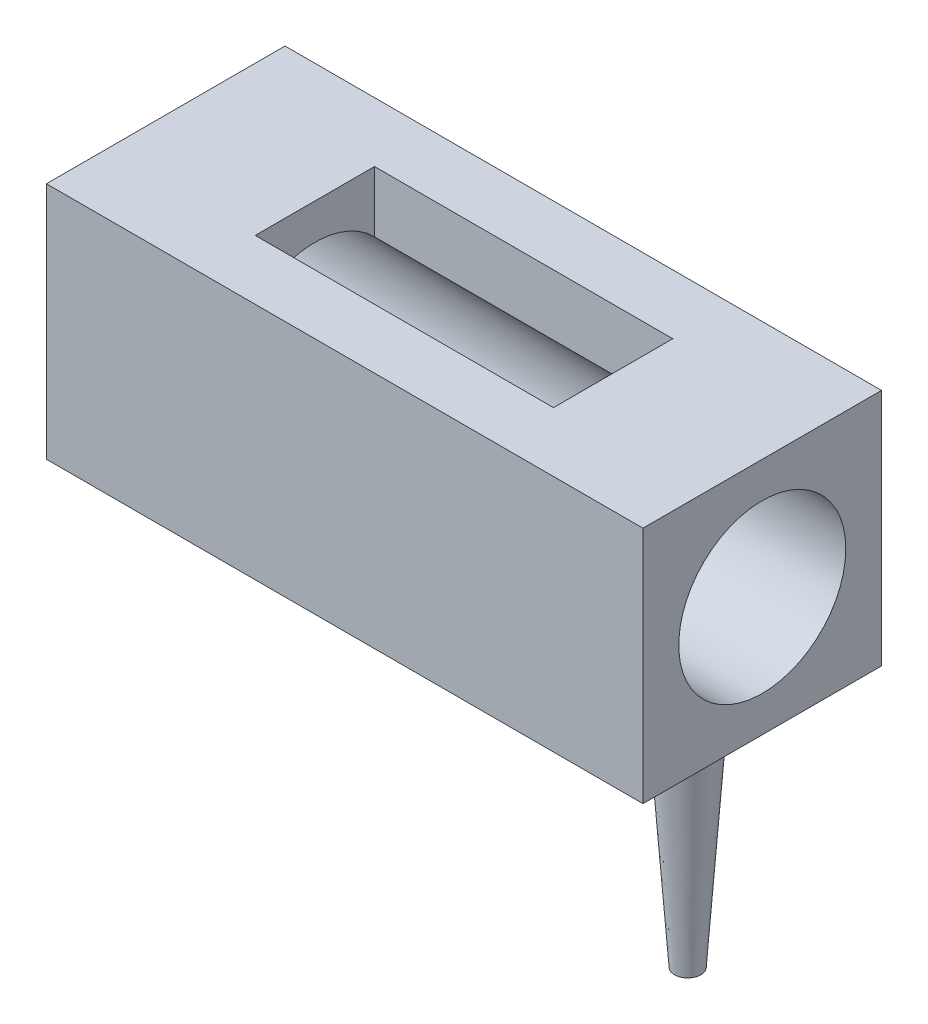
SolidWorks part; units mm, degrees
ref_plane "Alzado" through (0, 0, 0) normal (0, 0, 1) x (1, 0, 0)
ref_plane "Planta" through (0, 0, 0) normal (0, 1, 0) x (1, 0, 0)
ref_plane "Vista lateral" through (0, 0, 0) normal (1, 0, 0) x (0, 0, -1)
sketch "Croquis1" plane through (0, 0, 0) normal (0, 0, 1) x (1, 0, 0)
  line L1 (0, 0) -> (1000, 0)
  line L2 (0, 0) -> (0, 400)
  line L3 (0, 400) -> (1000, 400)
  line L4 (1000, 0) -> (1000, 400)
  dimension "D1" = 400
  dimension "D2" = 1000
extrude "Saliente-Extruir1" add sketch "Croquis1" along normal blind 400
sketch "Croquis2" plane through (1000, 0, 0) normal (1, 0, 0) x (0, 0, -1)
  line L0 (-400, 0) -> (-400, 400) construction
  line L1 (-400, 400) -> (0, 400) construction
  circle A0 centre (-200, 200) radius 140
  point P4 (0, 0)
  point P5 (0, 0)
  point P6 (0, 0)
  dimension "D1" = 200
  dimension "D2" = 200
extrude "Cortar-Extruir1" cut sketch "Croquis2" against normal blind 1000 contours A0
sketch "Croquis3" plane through (0, 0, 0) normal (0, -1, 0) x (1, 0, 0)
  line L0 (0, 400) -> (0, 0) construction
  line L1 (250, 300) -> (750, 300)
  line L2 (250, 300) -> (250, 100)
  line L3 (250, 100) -> (750, 100)
  line L4 (750, 300) -> (750, 100)
  line L5 (0, 0) -> (1000, 0) construction
  dimension "D1" = 500
  dimension "D2" = 200
  dimension "D3" = 250
  dimension "D4" = 100
extrude "Cortar-Extruir2" cut sketch "Croquis3" against normal blind 400
sketch "Croquis4" plane through (0, 0, 0) normal (0, -1, 0) x (1, 0, 0)
  line L0 (1000, 400) -> (1000, 0) construction
  line L1 (0, 0) -> (1000, 0) construction
  circle A0 centre (875, 200) radius 50
  point P2 (0, 0)
  point P5 (0, 0)
  dimension "D1" = 125
  dimension "D2" = 200
extrude "Saliente-Extruir2" add sketch "Croquis4" along normal blind 400 draft 4 contours A0
